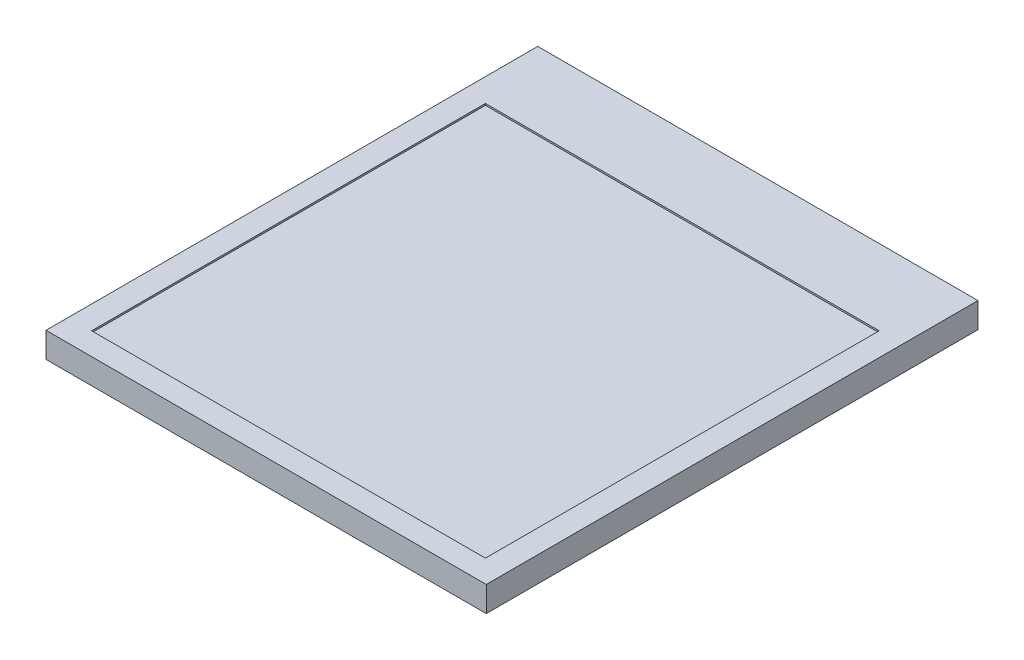
SolidWorks part; units mm, degrees
ref_plane "前视基准面" through (0, 0, 0) normal (0, 0, 1) x (1, 0, 0)
ref_plane "上视基准面" through (0, 0, 0) normal (0, 1, 0) x (1, 0, 0)
ref_plane "右视基准面" through (0, 0, 0) normal (1, 0, 0) x (0, 0, -1)
other "Configuration Table"
sketch "草图1" plane through (0, 0, 0) normal (0, 1, 0) x (1, 0, 0)
  line L1 (-13.08, -14.61) -> (13.08, -14.61)
  line L2 (-13.08, -14.61) -> (-13.08, 14.61)
  line L3 (-13.08, 14.61) -> (13.08, 14.61)
  line L4 (13.08, -14.61) -> (13.08, 14.61)
  line L5 (-13.08, -14.61) -> (13.08, 14.61) construction
  line L6 (-13.08, 14.61) -> (13.08, -14.61) construction
  point P0 (0, 0)
  dimension "D1" = 26.16
  dimension "D2" = 29.22
extrude "凸台-拉伸1" add sketch "草图1" along normal blind 1.5
sketch "草图3" plane through (-13.08, 0, 0) normal (-1, 0, 0) x (0, 0, 1)
  line L0 (-14.61, 0) -> (-14.8642, 0)
  line L1 (-14.8642, -1.6) -> (-3.11, -1.6)
  line L2 (-3.11, -1.6) -> (-3.11, -1.8)
  line L3 (-3.11, -1.8) -> (-14.8642, -1.8)
  line L4 (-14.8642, 0.2) -> (-14.61, 0.2)
  line L5 (-14.61, 1.5) -> (-14.61, 0) construction
  line L6 (-14.61, 0.2) -> (-14.61, 0)
  line L7 (-14.61, 0) -> (14.61, 0) construction
  arc A0 (-14.8642, 0) -> (-14.8642, -1.6) centre (-14.8642, -0.8) ccw
  arc A1 (-14.8642, -1.8) -> (-14.8642, 0.2) centre (-14.8642, -0.8) cw
  dimension "D1" = 0.2
  dimension "D2" = 11.5
  dimension "D3" = 1.6
extrude "凸台-拉伸2" add sketch "草图3" against normal offset from surface (15.86 mm away) 10.3 up to face at (13.08, 0.75, 0)
sketch "草图4" plane through (0, -1.8, 0) normal (0, -1, 0) x (1, 0, 0)
  line L0 (2.78, -3.11) -> (2.78, -14.8642) construction
  line L1 (-13.08, -3.11) -> (-8.62, -3.11)
  line L2 (-13.08, -3.11) -> (-13.08, -6.11)
  line L3 (-13.08, -6.11) -> (-8.62, -6.11)
  line L4 (-8.62, -3.11) -> (-8.62, -6.11)
  dimension "D1" = 11.4
  dimension "D2" = 3
extrude "切除-拉伸1" cut sketch "草图4" against normal blind 1
fillet "圆角2" radius 1 4 edges at (2.78, -1.7, -3.11) (-13.08, -1.7, -6.11) (-8.62, -1.7, -6.11) (-8.62, -1.7, -3.11)
sketch "草图5" plane through (0, 1.5, 0) normal (0, 1, 0) x (1, 0, 0)
  line L0 (0, -1.58) -> (0, 0) construction
  line L1 (-11.7, -13.28) -> (11.7, -13.28)
  line L2 (-11.7, -13.28) -> (-11.7, 10.12)
  line L3 (-11.7, 10.12) -> (11.7, 10.12)
  line L4 (11.7, -13.28) -> (11.7, 10.12)
  line L5 (-11.7, -13.28) -> (11.7, 10.12) construction
  line L6 (-11.7, 10.12) -> (11.7, -13.28) construction
  line L7 (-13.08, -14.61) -> (13.08, -14.61) construction
  point P0 (0, -1.58)
  dimension "D1" = 23.4
  dimension "D2" = 23.4
  dimension "D3" = 1.33
extrude "切除-拉伸2" cut sketch "草图5" against normal blind 0.1
sketch "草图6" plane through (0, -1.8, 0) normal (0, -1, 0) x (1, 0, 0)
  line L0 (1.78, -3.11) -> (-7.62, -3.11) construction
  line L1 (-6.94, -3.11) -> (-6.59, -3.11)
  line L2 (-6.94, -3.11) -> (-6.94, -6.11)
  line L3 (-6.94, -6.11) -> (-6.59, -6.11)
  line L4 (-6.59, -3.11) -> (-6.59, -6.11)
  line L5 (-6.24, -3.11) -> (-6.24, -6.11)
  line L6 (-6.24, -3.11) -> (-5.89, -3.11)
  line L7 (-5.89, -3.11) -> (-5.89, -6.11)
  line L8 (-6.24, -6.11) -> (-5.89, -6.11)
  line L9 (-5.54, -3.11) -> (-5.54, -6.11)
  line L10 (-5.54, -3.11) -> (-5.19, -3.11)
  line L11 (-5.19, -3.11) -> (-5.19, -6.11)
  line L12 (-5.54, -6.11) -> (-5.19, -6.11)
  line L13 (-4.84, -3.11) -> (-4.84, -6.11)
  line L14 (-4.84, -3.11) -> (-4.49, -3.11)
  line L15 (-4.49, -3.11) -> (-4.49, -6.11)
  line L16 (-4.84, -6.11) -> (-4.49, -6.11)
  line L17 (-4.14, -3.11) -> (-4.14, -6.11)
  line L18 (-4.14, -3.11) -> (-3.79, -3.11)
  line L19 (-3.79, -3.11) -> (-3.79, -6.11)
  line L20 (-4.14, -6.11) -> (-3.79, -6.11)
  line L21 (-3.44, -3.11) -> (-3.44, -6.11)
  line L22 (-3.44, -3.11) -> (-3.09, -3.11)
  line L23 (-3.09, -3.11) -> (-3.09, -6.11)
  line L24 (-3.44, -6.11) -> (-3.09, -6.11)
  line L25 (-2.74, -3.11) -> (-2.74, -6.11)
  line L26 (-2.74, -3.11) -> (-2.39, -3.11)
  line L27 (-2.39, -3.11) -> (-2.39, -6.11)
  line L28 (-2.74, -6.11) -> (-2.39, -6.11)
  line L29 (-2.04, -3.11) -> (-2.04, -6.11)
  line L30 (-2.04, -3.11) -> (-1.69, -3.11)
  line L31 (-1.69, -3.11) -> (-1.69, -6.11)
  line L32 (-2.04, -6.11) -> (-1.69, -6.11)
  line L33 (-1.34, -3.11) -> (-1.34, -6.11)
  line L34 (-1.34, -3.11) -> (-0.99, -3.11)
  line L35 (-0.99, -3.11) -> (-0.99, -6.11)
  line L36 (-1.34, -6.11) -> (-0.99, -6.11)
  line L37 (-0.64, -3.11) -> (-0.64, -6.11)
  line L38 (-0.64, -3.11) -> (-0.29, -3.11)
  line L39 (-0.29, -3.11) -> (-0.29, -6.11)
  line L40 (-0.64, -6.11) -> (-0.29, -6.11)
  line L41 (0.06, -3.11) -> (0.06, -6.11)
  line L42 (0.06, -3.11) -> (0.41, -3.11)
  line L43 (0.41, -3.11) -> (0.41, -6.11)
  line L44 (0.06, -6.11) -> (0.41, -6.11)
  line L45 (0.76, -3.11) -> (0.76, -6.11)
  line L46 (0.76, -3.11) -> (1.11, -3.11)
  line L47 (1.11, -3.11) -> (1.11, -6.11)
  line L48 (0.76, -6.11) -> (1.11, -6.11)
  line L49 (-8.62, -5.11) -> (-8.62, -4.11) construction
  dimension "D1" = 3
  dimension "D2" = 0.35
  dimension "D4" = 1.68
  dimension "D5" = 0.7
  dimension "D3" = 12
extrude "切除-拉伸3" cut sketch "草图6" against normal blind 0.005
